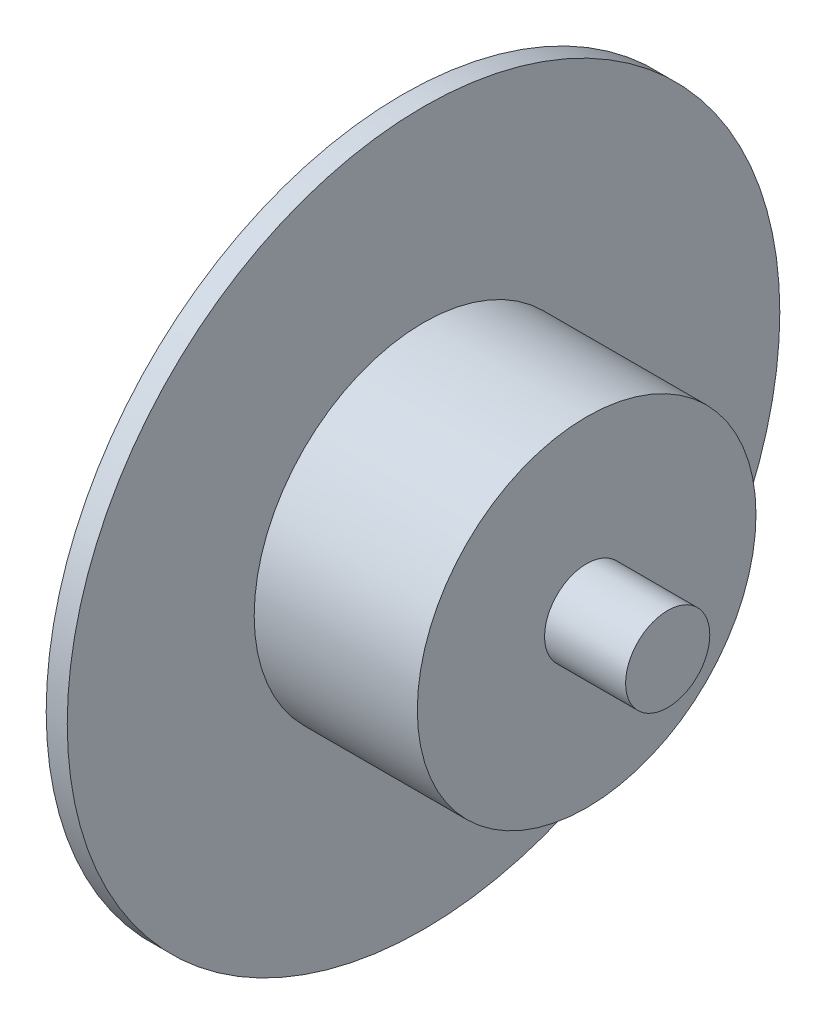
SolidWorks part; units mm, degrees
ref_plane "Front Plane" through (0, 0, 0) normal (0, 0, 1) x (1, 0, 0)
ref_plane "Top Plane" through (0, 0, 0) normal (0, 1, 0) x (1, 0, 0)
ref_plane "Right Plane" through (0, 0, 0) normal (1, 0, 0) x (0, 0, -1)
sketch "Sketch1" plane through (0, 0, 0) normal (1, 0, 0) x (0, 0, -1)
  circle A0 centre (0, 0) radius 50
  dimension "D1" = 100
extrude "Boss-Extrude1" add sketch "Sketch1" along normal blind 140
sketch "Sketch2" plane through (0, 0, 0) normal (0, 1, 0) x (1, 0, 0)
  line L0 (0, 0) -> (140, 0) construction
  line L1 (0, 50) -> (0, -50) construction
  line L2 (140, -50) -> (140, 50) construction
  line L3 (20, 60) -> (20, 0)
  line L4 (70, 50) -> (70, -150.463) construction
  line L5 (140, 50) -> (0, 50) construction
  line L6 (20, 60) -> (10, 60)
  line L7 (10, 60) -> (10, 0)
  line L8 (10, 0) -> (20, 0)
  line L9 (130, 0) -> (120, 0)
  line L10 (120, 60) -> (130, 60)
  line L11 (120, 60) -> (120, 0)
  line L12 (130, 60) -> (130, 0)
  dimension "D1" = 10
  dimension "D2" = 50
  dimension "D3" = 60
revolve "Revolve1" add sketch "Sketch2" angle 360 about L0
sketch "Sketch3" plane through (0, 0, 0) normal (-1, 0, 0) x (0, 0, 1)
  circle A1 centre (0, 0) radius 50
  circle A2 centre (0, 0) radius 50
  dimension "D1" = 0
extrude "Boss-Extrude2" add sketch "Sketch3" along normal blind 100
sketch "Sketch4" plane through (-100, 0, 0) normal (-1, 0, 0) x (0, 0, 1)
  circle A0 centre (0, 0) radius 169.2682
  dimension "D1" = 338.5363
extrude "Boss-Extrude3" add sketch "Sketch4" along normal blind 10
fillet "Fillet2" radius 50 1 edges at (-100, 0, 50)
sketch "Sketch5" plane through (0, 0, 0) normal (0, 1, 0) x (1, 0, 0)
  line L0 (-100, -169.2682) -> (-100, 169.2682) construction
  line L1 (461.7068, -302.3842) -> (-100, -302.3842)
  line L2 (461.7068, -302.3842) -> (461.7068, 302.3842)
  line L3 (461.7068, 302.3842) -> (-100, 302.3842)
  line L4 (-100, -302.3842) -> (-100, 302.3842)
  line L5 (461.7068, -302.3842) -> (-100, 302.3842) construction
  line L6 (461.7068, 302.3842) -> (-100, -302.3842) construction
  point P0 (180.8534, 0)
extrude "Cut-Extrude1" cut sketch "Sketch5" against normal through all both and the other way through all
sketch "Sketch6" plane through (-100, 0, 0) normal (1, 0, 0) x (0, 0, -1)
  circle A0 centre (0, 0) radius 20
  dimension "D1" = 40
extrude "Boss-Extrude4" add sketch "Sketch6" along normal blind 116
sketch "Sketch7" plane through (0, 0, 0) normal (0, 1, 0) x (1, 0, 0)
  line L0 (-151.1541, 0) -> (150.3543, 0) construction
  line L1 (-100, 0) -> (-100, 80.4506)
  line L2 (-100, -169.2682) -> (-100, 169.2682) construction
  line L3 (-100, 80.4506) -> (-22.5, 80.4506)
  line L4 (-22.5, 80.4506) -> (-22.5, 0)
  line L5 (-22.5, 0) -> (-100, 0)
  line L6 (16, -20) -> (16, 20) construction
  dimension "D1" = 38.5
revolve "Revolve2" add sketch "Sketch7" angle 360 about L0
